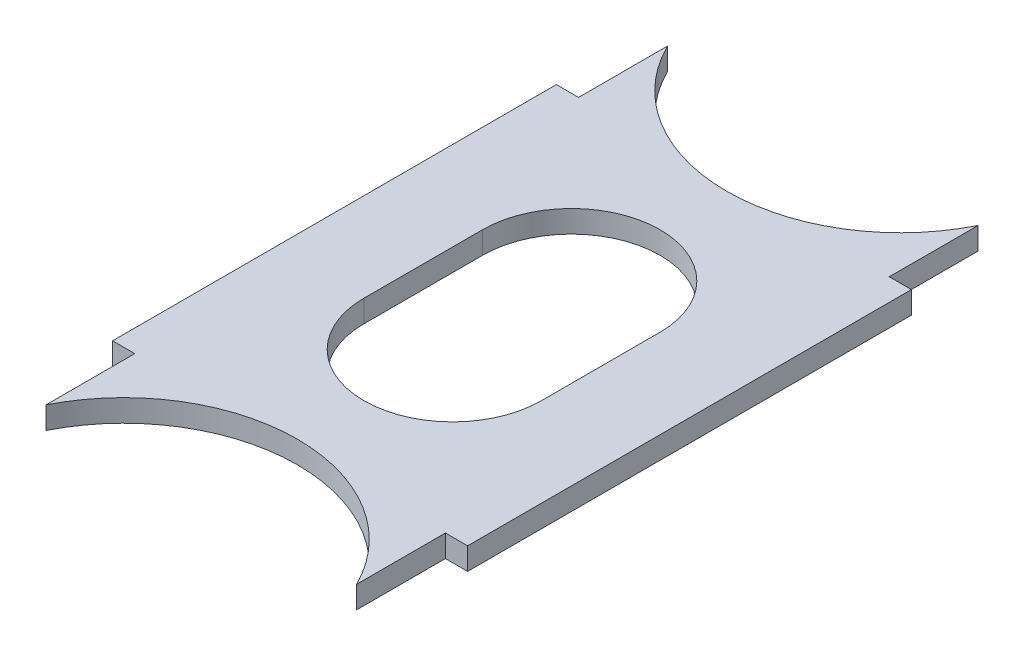
SolidWorks part; units mm, degrees
material "AISI 4130 Steel, annealed at 865C"
ref_plane "X-Y Datum" through (0, 0, 0) normal (0, 0, 1) x (1, 0, 0)
ref_plane "X-Z Datum" through (0, 0, 0) normal (0, 1, 0) x (1, 0, 0)
ref_plane "Y-Z Datum" through (0, 0, 0) normal (1, 0, 0) x (0, 0, -1)
sketch "Sketch1" plane through (0, 0, 0) normal (0, 1, 0) x (1, 0, 0)
  line L0 (11.1125, -15.875) -> (12.7, -15.875)
  line L1 (11.1125, 22.225) -> (-11.1125, 22.225) construction
  line L2 (11.1125, 22.225) -> (11.1125, -22.225)
  line L3 (11.1125, -22.225) -> (-11.1125, -22.225) construction
  line L4 (-11.1125, 22.225) -> (-11.1125, -22.225)
  line L5 (11.1125, 22.225) -> (-11.1125, -22.225) construction
  line L6 (11.1125, -22.225) -> (-11.1125, 22.225) construction
  line L7 (12.7, -15.875) -> (12.7, 15.875)
  line L8 (12.7, 15.875) -> (11.1125, 15.875)
  line L9 (0, -0.8731) -> (0, 0.8731) construction
  line L10 (-12.7, -15.875) -> (-12.7, 15.875)
  line L11 (-12.7, 15.875) -> (-11.1125, 15.875)
  line L12 (-11.1125, -15.875) -> (-12.7, -15.875)
  line L13 (0, 4.2446) -> (0, -4.2446) construction
  line L18 (6.35, 4.2446) -> (6.35, -4.2446)
  line L19 (-6.35, 4.2446) -> (-6.35, -4.2446)
  line L20 (0, -15.3571) -> (0, -10.5946) construction
  line L21 (6.35, 0) -> (11.1125, 0) construction
  arc A1 (11.1125, -22.225) -> (-11.1125, -22.225) centre (0, -27.7812) ccw
  arc A2 (-11.1125, 22.225) -> (11.1125, 22.225) centre (0, 27.7812) ccw
  arc A3 (6.35, 4.2446) -> (-6.35, 4.2446) centre (0, 4.2446) ccw
  arc A4 (-6.35, -4.2446) -> (6.35, -4.2446) centre (0, -4.2446) ccw
  point P0 (0, 0)
  point P12 (12.7, 0)
  point P19 (0, 0)
  point P22 (0, 0)
  dimension "D1" = 1.5875
  dimension "D2" = 31.75
  dimension "D3" = 22.225
  dimension "D4" = 44.45
  dimension "D5" = 4.7625
extrude "Boss-Extrude1" add sketch "Sketch1" along normal blind 1.5875
